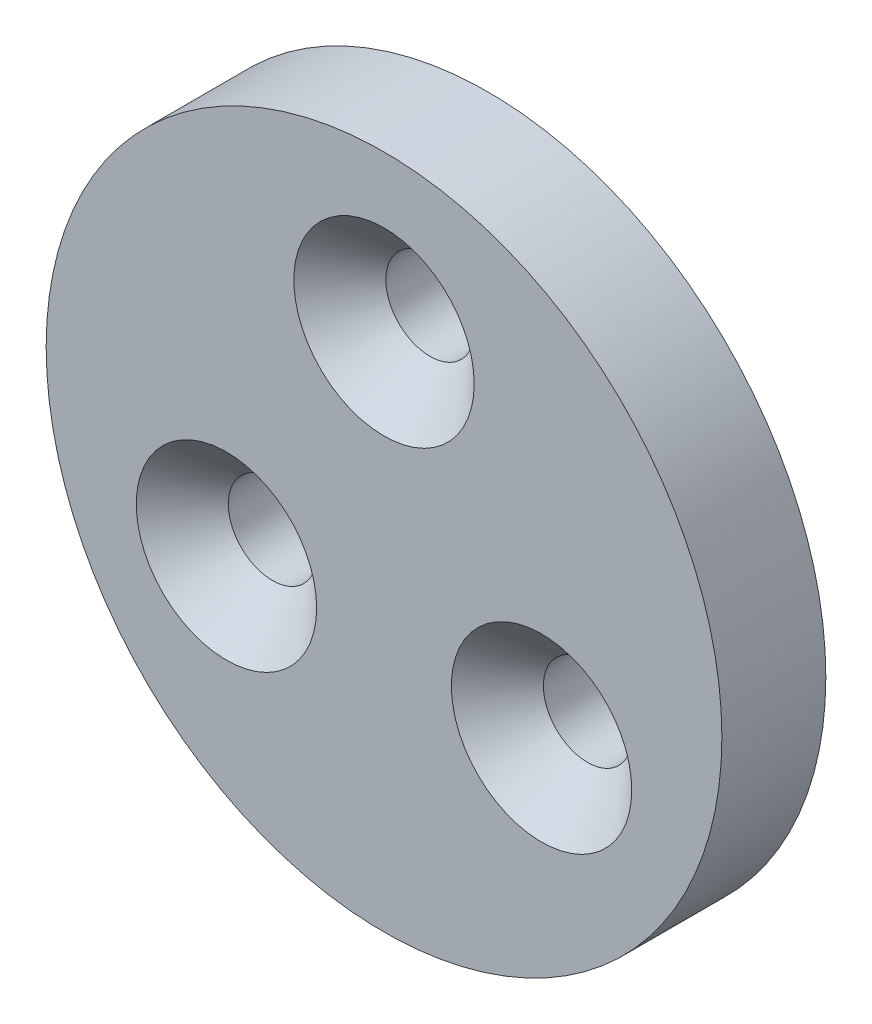
SolidWorks part; units mm, degrees
material "6061-T6 (SS)"
ref_plane "Front Plane" through (0, 0, 0) normal (0, 0, 1) x (1, 0, 0)
ref_plane "Top Plane" through (0, 0, 0) normal (0, 1, 0) x (1, 0, 0)
ref_plane "Right Plane" through (0, 0, 0) normal (1, 0, 0) x (0, 0, -1)
sketch "Sketch1" plane through (0, 0, 0) normal (0, 0, 1) x (1, 0, 0)
  circle A0 centre (0, 0) radius 13
  dimension "D1" = 26
extrude "Boss-Extrude1" add sketch "Sketch1" along normal blind 4
sketch "Sketch5" plane through (0, 0, 4) normal (0, 0, 1) x (1, 0, 0)
  point P4 (0, 7)
  point P11 (6.0622, -3.5)
  point P12 (-6.0622, -3.5)
  dimension "D2" = 3
hole_wizard "CSK for M3 Hex Socket Countersunk Head Screw1" positions "Sketch5" profile "Sketch7" countersink size "M3" standard "DIN"
sketch "Sketch7" plane through (0, 7, 4) normal (1, 0, 0) x (0, -1, 0)
  line L0 (0, 0) -> (0, 13.0215)
  line L1 (0, 13.0215) -> (1.7, 12)
  line L2 (1.7, 12) -> (1.7, 1.77)
  line L3 (1.7, 1.77) -> (3.47, 0)
  line L5 (3.47, 0) -> (0, 0)
  line L6 (-1.7, 1.77) -> (-3.47, 0) construction
  line L10 (0, 13.0215) -> (-1.7, 12) construction
  line L11 (0, -6.35) -> (0, 107.95) construction
  dimension "Hole Dia." = 3.4
  dimension "Hole Depth" = 12
  dimension "Near C'Sink Dia." = 6.94
  dimension "Near C'Sink Angle" = 90
  dimension "Drill Angle" = 118
